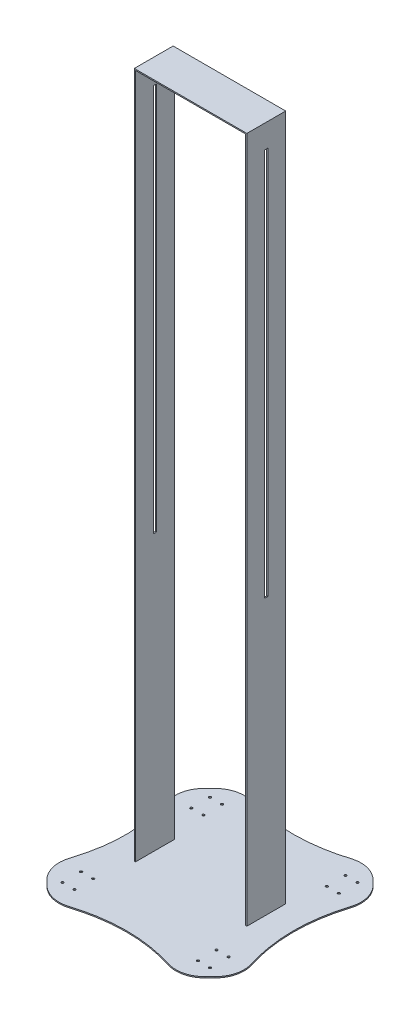
SolidWorks part; units mm, degrees
ref_plane "Front Plane" through (0, 0, 0) normal (0, 0, 1) x (1, 0, 0)
ref_plane "Top Plane" through (0, 0, 0) normal (0, 1, 0) x (1, 0, 0)
ref_plane "Right Plane" through (0, 0, 0) normal (1, 0, 0) x (0, 0, -1)
sketch "Sketch1" plane through (0, 0, 0) normal (0, 0, 1) x (1, 0, 0)
  line L1 (-145, 1.5) -> (145, 1.5)
  line L2 (-145, 1.5) -> (-145, -1.5)
  line L3 (-145, -1.5) -> (145, -1.5)
  line L4 (145, 1.5) -> (145, -1.5)
  line L5 (-145, 1.5) -> (145, -1.5) construction
  line L6 (-145, -1.5) -> (145, 1.5) construction
  point P0 (0, 0)
  dimension "D1" = 3
  dimension "D2" = 290
extrude "Boss-Extrude1" add sketch "Sketch1" against normal blind 100
sketch "Sketch2" plane through (0, -1.5, 0) normal (0, -1, 0) x (1, 0, 0)
  line L0 (-145, -100) -> (145, -100) construction
  line L1 (-145, 0) -> (-142, 0)
  line L2 (-145, 0) -> (-145, -100)
  line L3 (-145, -100) -> (-142, -100)
  line L4 (-142, 0) -> (-142, -100)
  line L5 (0, 0) -> (0, -100)
  line L6 (145, -100) -> (142, -100)
  line L7 (142, 0) -> (142, -100)
  line L8 (145, 0) -> (142, 0)
  line L9 (145, 0) -> (145, -100)
  dimension "D1" = 3
extrude "Boss-Extrude2" add sketch "Sketch2" along normal blind 1765.8 contours L4 L3 L2 L1 | L9 L6 L7 L8
sketch "Sketch5" plane through (0, 0, 0) normal (1, 0, 0) x (0, 0, -1)
  line L0 (50, 2.4141) -> (50, -1835.5207) construction
  line L1 (0, -1767.3) -> (0, 1.5) construction
  line L2 (100, 1.5) -> (0, 1.5) construction
  line L3 (54, -1058.5) -> (46, -1058.5)
  line L4 (54, -1058.5) -> (54, -58.5)
  line L5 (54, -58.5) -> (46, -58.5)
  line L6 (46, -1058.5) -> (46, -58.5)
  line L7 (54, -1058.5) -> (46, -58.5) construction
  line L8 (54, -58.5) -> (46, -1058.5) construction
  point P4 (50, -558.5)
  dimension "D1" = 50
  dimension "D2" = 8
  dimension "D3" = 4
  dimension "D4" = 60
  dimension "D5" = 1000
extrude "Cut-Extrude1" cut sketch "Sketch5" against normal mid plane 300
sketch "Sketch6" plane through (0, -1767.3, 0) normal (0, -1, 0) x (1, 0, 0)
  line L0 (0, 0) -> (0, -100) construction
  line L1 (-250, 200) -> (250, 200) construction
  line L2 (-250, 200) -> (-250, -300) construction
  line L3 (-250, -300) -> (250, -300) construction
  line L4 (250, 200) -> (250, -300) construction
  line L5 (-250, 200) -> (250, -300) construction
  line L6 (-250, -300) -> (250, 200) construction
  line L7 (-142, -100) -> (142, -100) construction
  line L8 (-250, 120) -> (-170, 200)
  line L9 (170, 200) -> (250, 120)
  line L10 (250, -220) -> (170, -300)
  line L11 (-170, -300) -> (-250, -220)
  spline S0 degree 2 poles (-170, 200) (0, 130) (170, 200) knots 0 0 0 1 1 1
  spline S1 degree 2 poles (250, 120) (180, -50) (250, -220) knots 0 0 0 1 1 1
  spline S2 degree 2 poles (-170, -300) (0, -230) (170, -300) knots 0 0 0 1 1 1
  spline S3 degree 3 poles (-250, 120) (-201.6183, -7.1799) (-205.0484, -92.8201) (-250, -220) knots 0 0 0 0 1 1 1 1
  point P0 (0, -50)
  point P12 (0, 200)
  point P14 (0, -100)
  point P18 (0, -50)
  point P19 (250, -50)
  point P23 (0, -300)
  point P28 (-250, -50)
  dimension "D1" = 500
  dimension "D2" = 500
  dimension "D3" = 0
  dimension "D4" = 35
  dimension "D5" = 35
  dimension "D6" = 35
  dimension "D7" = 35
  dimension "D8" = 80
  dimension "D9" = 80
  dimension "D10" = 80
  dimension "D11" = 80
  dimension "D12" = 80
  dimension "D13" = 80
  dimension "D14" = 80
  dimension "D15" = 80
extrude "Boss-Extrude3" add sketch "Sketch6" along normal blind 3
fillet "Fillet1" radius 75 8 edges at (250, -1768.8, 120) (-170, -1768.8, 200) (-250, -1768.8, 120) (-250, -1768.8, -220) (-170, -1768.8, -300) (170, -1768.8, -300) (250, -1768.8, -220) (170, -1768.8, 200)
sketch "Sketch7" plane through (0, -1770.3, 0) normal (0, -1, 0) x (1, 0, 0)
  line L0 (0, 200) -> (0, -300) construction
  line L1 (-250, -50) -> (250, -50) construction
  circle A0 centre (-190, 140) radius 3
  circle A1 centre (-159, 140) radius 3
  circle A2 centre (-190, 92) radius 3
  circle A3 centre (-159, 92) radius 3
  circle A4 centre (190, 92) radius 3
  circle A5 centre (159, 92) radius 3
  circle A6 centre (159, 140) radius 3
  circle A7 centre (190, 140) radius 3
  circle A8 centre (159, -192) radius 3
  circle A9 centre (190, -192) radius 3
  circle A10 centre (190, -240) radius 3
  circle A11 centre (159, -240) radius 3
  circle A12 centre (-190, -192) radius 3
  circle A13 centre (-159, -192) radius 3
  circle A14 centre (-159, -240) radius 3
  circle A15 centre (-190, -240) radius 3
  point P8 (0, -50)
  point P9 (0, -50)
  dimension "D1" = 6
  dimension "D2" = 31
  dimension "D3" = 48
  dimension "D4" = 190
  dimension "D5" = 500
  dimension "D6" = 50
  dimension "D7" = 500
  dimension "D8" = 190
extrude "Cut-Extrude2" cut sketch "Sketch7" against normal blind 10
